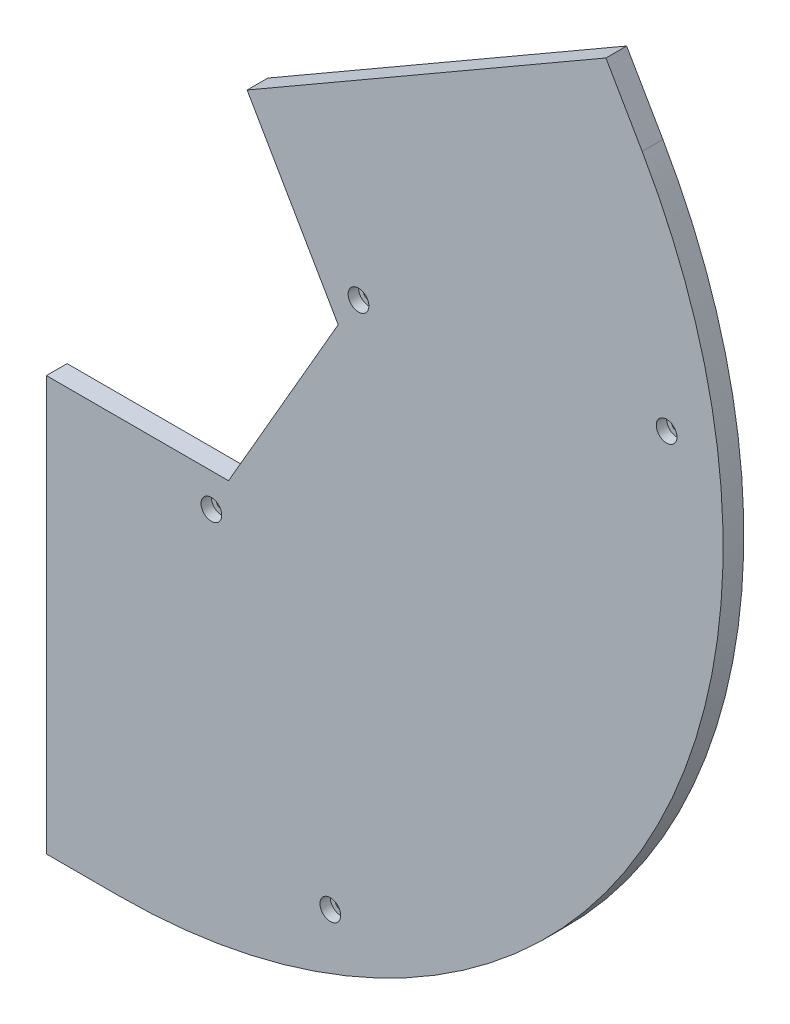
SolidWorks part; units mm, degrees
material "ABS"
ref_plane "前基準面" through (0, 0, 0) normal (0, 0, 1) x (1, 0, 0)
ref_plane "上基準面" through (0, 0, 0) normal (0, 1, 0) x (1, 0, 0)
ref_plane "右基準面" through (0, 0, 0) normal (1, 0, 0) x (0, 0, -1)
sketch "草圖1" plane through (0, 0, 0) normal (0, 0, 1) x (1, 0, 0)
  line L0 (0, 0) -> (0, -175)
  line L1 (0, 0) -> (151.5544, 87.5)
  arc A0 (151.5544, 87.5) -> (0, -175) centre (0, 0) cw
  dimension "D1" = 175
  dimension "D2" = 120
extrude "填料-伸長1" add sketch "草圖1" along normal blind 6
sketch "草圖2" plane through (0, 0, 6) normal (0, 0, 1) x (1, 0, 0)
  line L0 (0, -55) -> (31.7543, -55)
  line L1 (31.7543, -55) -> (63.5085, 0)
  line L2 (63.5085, 0) -> (31.7543, 55)
  line L3 (31.7543, 55) -> (0, 55)
  circle A0 centre (0, 0) radius 55
  line M5 (151.5544, 87.5) -> (0, 0)
  line M6 (0, 0) -> (0, -175)
  dimension "D1" = 110
  dimension "D2" = 120
extrude "除料-伸長1" cut sketch "草圖2" against normal through all contours A0 M6 M5 | A0 L0 L1 | A0 L1 L2
sketch "草圖3" plane through (0, 0, 0) normal (-1, 0, 0) x (0, 0, 1)
  line L4 (6, -175) -> (6, -55)
  line L5 (6, -55) -> (0, -55)
  line L6 (0, -55) -> (0, -175)
  line L7 (0, -175) -> (6, -175)
  line L8 (6, -175) -> (6, -55)
  line L9 (6, -55) -> (0, -55)
  line L10 (0, -55) -> (0, -175)
  line L11 (0, -175) -> (6, -175)
  dimension "D1" = 0
extrude "填料-伸長2" add sketch "草圖3" along normal blind 21
sketch "草圖4" plane through (0, 0, 0) normal (-0.5, 0.866, 0) x (0.866, 0.5, 0)
  line L4 (175, 0) -> (55, 0)
  line L5 (55, 0) -> (55, -6)
  line L6 (55, -6) -> (175, -6)
  line L7 (175, -6) -> (175, 0)
  line L8 (175, 0) -> (55, 0)
  line L9 (55, 0) -> (55, -6)
  line L10 (55, -6) -> (175, -6)
  line L11 (175, -6) -> (175, 0)
  dimension "D1" = 0
extrude "填料-伸長3" add sketch "草圖4" along normal blind 21
sketch "草圖5" plane through (0, 0, 6) normal (0, 0, 1) x (1, 0, 0)
  line L0 (0, 0) -> (66.9696, -161.6789) construction
  line L1 (0, 0) -> (173.5029, 22.8421) construction
  line L2 (0, 0) -> (151.5544, -87.5) construction
  arc A0 (0, -175) -> (151.5544, 87.5) centre (0, 0) ccw construction
  circle A2 centre (61.2293, -147.8207) radius 1.6
  circle A3 centre (26.7878, -64.6716) radius 1.6
  circle A8 centre (158.6312, 20.8842) radius 1.6
  circle A9 centre (69.4011, 9.1368) radius 1.6
  dimension "D2" = 3.2
  dimension "D3" = 90
  dimension "D4" = 160
  dimension "D1" = 75
extrude "除料-伸長2" cut sketch "草圖5" against normal through all
sketch "草圖6" plane through (0, 0, 6) normal (0, 0, 1) x (1, 0, 0)
  circle A0 centre (61.2293, -147.8207) radius 3
  circle A1 centre (26.7878, -64.6716) radius 3
  circle A2 centre (69.4011, 9.1368) radius 3
  circle A3 centre (158.6312, 20.8842) radius 3
  dimension "D1" = 6
extrude "除料-伸長3" cut sketch "草圖6" against normal blind 3
